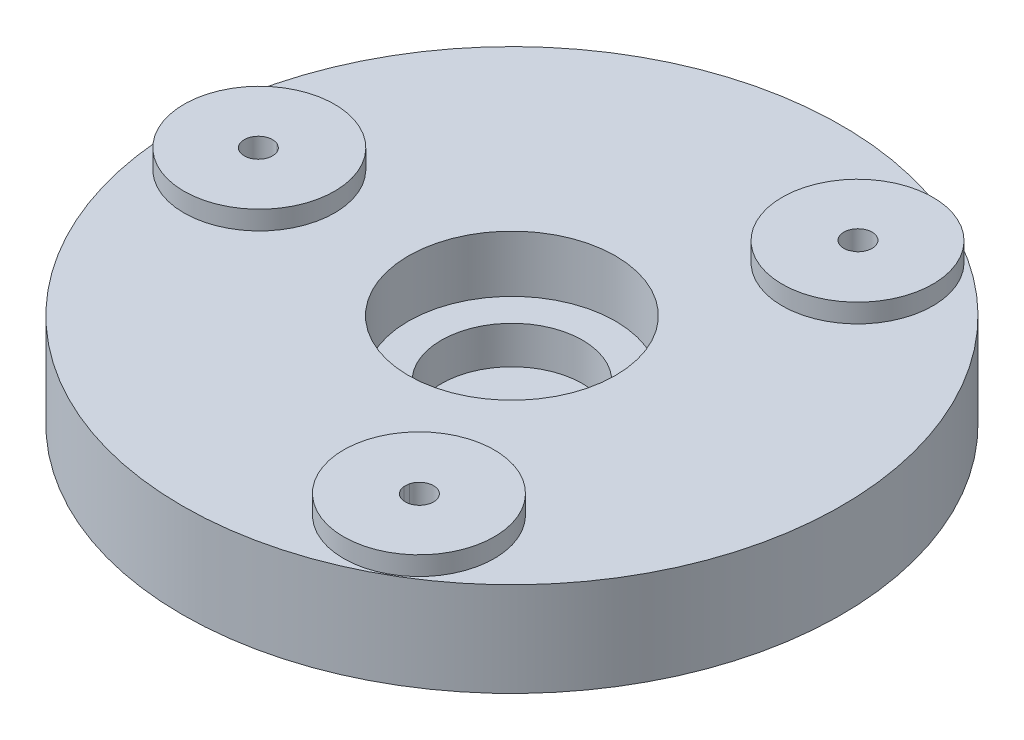
SolidWorks part; units mm, degrees
ref_plane "Front Plane" through (0, 0, 0) normal (0, 0, 1) x (1, 0, 0)
ref_plane "Top Plane" through (0, 0, 0) normal (0, 1, 0) x (1, 0, 0)
ref_plane "Right Plane" through (0, 0, 0) normal (1, 0, 0) x (0, 0, -1)
sketch "Sketch1" plane through (0, 0, 0) normal (0, 1, 0) x (1, 0, 0)
  circle A0 centre (0, 0) radius 35
extrude "Boss-Extrude1" add sketch "Sketch1" against normal blind 10
sketch "Sketch2" plane through (0, 0, 0) normal (0, 1, 0) x (1, 0, 0)
  circle A0 centre (0, 0) radius 11
extrude "Cut-Extrude1" cut sketch "Sketch2" against normal blind 6
sketch "Sketch3" plane through (0, -10, 0) normal (0, -1, 0) x (1, 0, 0)
  circle A0 centre (0, 0) radius 7.5
extrude "Cut-Extrude2" cut sketch "Sketch3" against normal blind 6
sketch "Sketch4" plane through (0, 0, 0) normal (0, 1, 0) x (1, 0, 0)
  circle A0 centre (13.4561, 23.2459) radius 8
extrude "Boss-Extrude2" add sketch "Sketch4" along normal blind 2
sketch "Sketch5" plane through (0, 2, 0) normal (0, 1, 0) x (1, 0, 0)
  line L0 (12.804, 24.6462) -> (14.0714, 21.9752) construction
  line L1 (14.3957, 22.1291) -> (13.7471, 21.8213)
  circle A0 centre (13.4377, 23.3107) radius 1.5
  point P8 (14.0714, 21.9752)
extrude "Cut-Extrude3" cut sketch "Sketch5" against normal blind 21
sketch "Sketch6" plane through (0, -10, 0) normal (0, -1, 0) x (1, 0, 0)
  circle A0 centre (13.4377, -23.3107) radius 3.1
extrude "Cut-Extrude4" cut sketch "Sketch6" against normal blind 4
pattern_circular "CirPattern1" count 3 over 360 about axis through (0, 0, 0) along (0, 1, 0) of "Boss-Extrude2"
pattern_circular "CirPattern2" count 3 over 360 about axis through (0, 0, 0) along (0, 1, 0) of "Cut-Extrude3"
pattern_circular "CirPattern3" count 2 every 30 about axis through (0, -4, 0) along (0, -1, 0) of "Cut-Extrude4"
pattern_circular "CirPattern4" count 2 every 30 about axis through (0, -10, 0) along (0, 1, 0) of "Cut-Extrude4"
pattern_circular "CirPattern5" count 3 over 360 about axis through (0, 0, 0) along (0, 1, 0) of "CirPattern4", "CirPattern3", "Cut-Extrude4"
sketch "Sketch7" plane through (0, -10, 0) normal (0, -1, 0) x (1, 0, 0)
  circle A0 centre (0, 0) radius 8.9656
extrude "Boss-Extrude3" add sketch "Sketch7" along normal blind 10 separate body
sketch "Sketch8" plane through (0, -20, 0) normal (0, -1, 0) x (1, 0, 0)
  line L1 (9.9656, -1) -> (7.9656, -1)
  line L2 (9.9656, -1) -> (9.9656, 1)
  line L3 (9.9656, 1) -> (7.9656, 1)
  line L4 (7.9656, -1) -> (7.9656, 1)
  line L5 (9.9656, -1) -> (7.9656, 1) construction
  line L6 (9.9656, 1) -> (7.9656, -1) construction
  circle A0 centre (0, 0) radius 8.9656 construction
  point P0 (8.9656, 0)
extrude "Cut-Extrude5" cut sketch "Sketch8" against normal blind 10
